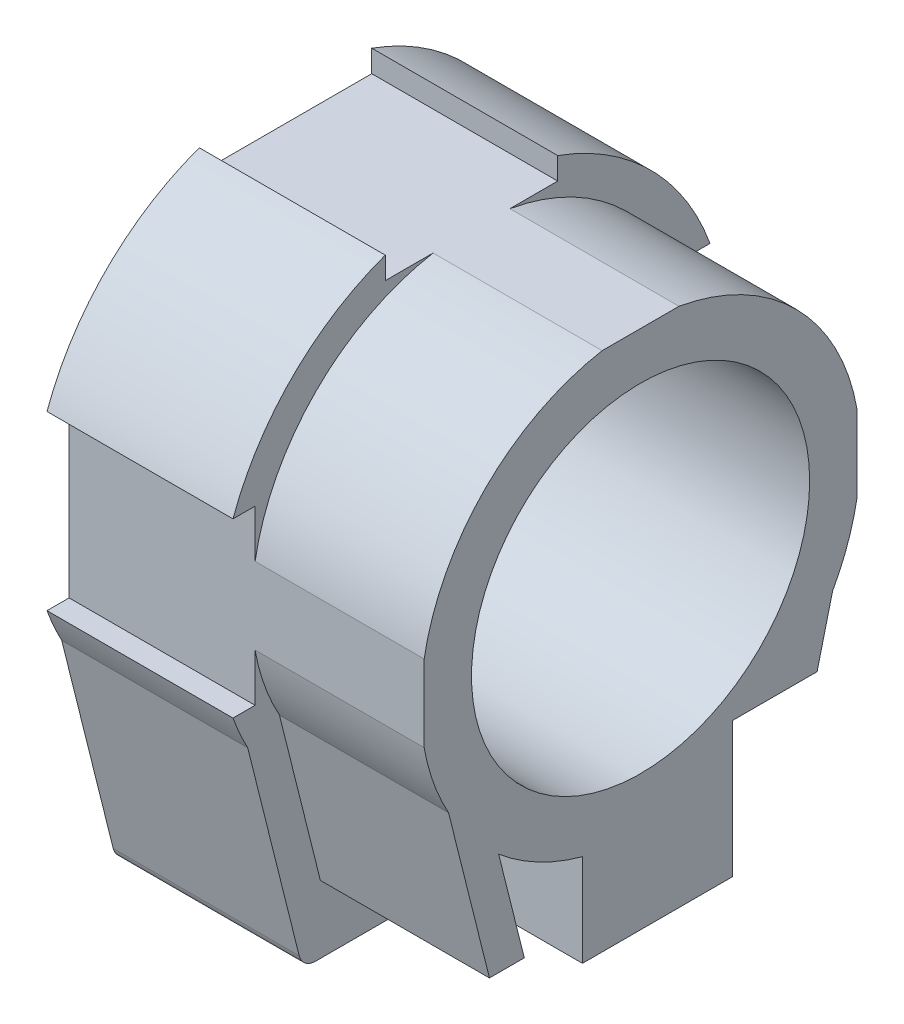
SolidWorks part; units mm, degrees
ref_plane "Alzado" through (0, 0, 0) normal (0, 0, 1) x (1, 0, 0)
ref_plane "Planta" through (0, 0, 0) normal (0, 1, 0) x (1, 0, 0)
ref_plane "Vista lateral" through (0, 0, 0) normal (1, 0, 0) x (0, 0, -1)
sketch "Croquis1" plane through (0, 0, 0) normal (1, 0, 0) x (0, 0, -1)
  line L0 (-15, 35) -> (-15, 30) construction
  line L1 (-5.7808, 0) -> (-24.2192, 0)
  line L5 (-15, 30) -> (-15, 10) construction
  line L6 (-25, 20) -> (-25, 0) construction
  line L7 (-5, 20) -> (-5, 0) construction
  line L8 (-28.2353, 12.9412) -> (-25.1894, 0.7575)
  line L9 (-1.7647, 12.9412) -> (-4.8106, 0.7575)
  circle A0 centre (-15, 20) radius 10
  arc A1 (-1.7647, 12.9412) -> (-28.2353, 12.9412) centre (-15, 20) ccw
  arc A2 (-24.2192, 0) -> (-25.1894, 0.7575) centre (-24.2192, 1) cw
  arc A3 (-5.7808, 0) -> (-4.8106, 0.7575) centre (-5.7808, 1) ccw
  dimension "D1" = 1
  dimension "D2" = 35
  dimension "D3" = 20
  dimension "D4" = 5
extrude "Saliente-Extruir1" add sketch "Croquis1" along normal blind 11
sketch "Croquis2" plane through (11, 0, 0) normal (1, 0, 0) x (0, 0, -1)
  line L9 (-23.4384, 2) -> (-6.5616, 2)
  line L10 (-6.5616, 2) -> (-3.6431, 13.6738)
  line L11 (-26.3569, 13.6738) -> (-23.4384, 2)
  line L12 (-23.4384, 2) -> (-6.5616, 2)
  line L13 (-6.5616, 2) -> (-3.6431, 13.6738)
  line L14 (-26.3569, 13.6738) -> (-23.4384, 2)
  circle A6 centre (-15, 20) radius 10 construction
  circle A7 centre (-15, 20) radius 10
  arc A9 (-3.6431, 13.6738) -> (-26.3569, 13.6738) centre (-15, 20) ccw
  arc A10 (-3.6431, 13.6738) -> (-26.3569, 13.6738) centre (-15, 20) ccw
  dimension "D1" = 2
extrude "Saliente-Extruir2" add sketch "Croquis2" along normal blind 10
sketch "Croquis3" plane through (21, 0, 0) normal (1, 0, 0) x (0, 0, -1)
  line L0 (-9.5616, 2) -> (-9.5616, 10)
  line L1 (-23.4384, 2) -> (-6.5616, 2) construction
  line L2 (-9.5616, 10) -> (-4.5616, 10)
  line L3 (-6.5616, 2) -> (-3.6431, 13.6738) construction
  line L4 (-9.5616, 2) -> (-6.5616, 2)
  line L5 (-6.5616, 2) -> (-4.5616, 10)
  line L6 (-21.7673, 2) -> (-21.7673, 4) construction
  line L7 (-23.4384, 2) -> (-18.4384, 2)
  line L8 (-23.4384, 2) -> (-23.9384, 4)
  line L9 (-21.7673, 4) -> (-21.8769, 4) construction
  line L10 (-24.4166, 14.1589) -> (-21.4982, 2.4851)
  line L11 (-23.1946, 9.2708) -> (-21.8769, 4)
  line L12 (-21.8769, 4) -> (-23.9384, 4)
  line L13 (-26.3569, 13.6738) -> (-23.4384, 2) construction
  line L14 (-18.4384, 2) -> (-18.4384, 6.9452)
  line L15 (-23.1946, 9.2708) -> (-23.3955, 10.0745)
  line L16 (-18.4384, 6.9452) -> (-18.4384, 7.463)
  circle A6 centre (-15, 20) radius 13
  arc A7 (-23.3955, 10.0745) -> (-18.4384, 7.463) centre (-15, 20) ccw
  dimension "D2" = 8
  dimension "D3" = 5
  dimension "D4" = 2
  dimension "D6" = 5
  dimension "D5" = 2
  dimension "D7" = 3
extrude "Cortar-Extruir3" cut sketch "Croquis3" against normal blind 10
sketch "Croquis8" plane through (0, 2, 0) normal (0, -1, 0) x (1, 0, 0)
  line L1 (11, 14) -> (13.2177, 14) construction
  line L2 (11, 18.4384) -> (11, 9.5616) construction
  line L4 (14.45, 14) -> (16, 14) construction
  line L5 (16, 14) -> (17.55, 14) construction
  line L7 (17.55, 14) -> (21, 14) construction
  line L8 (21, 18.4384) -> (21, 9.5616) construction
  circle A0 centre (16, 14) radius 1.55
  dimension "D2" = 3.1
extrude "Cortar-Extruir4" cut sketch "Croquis8" against normal blind 5
sketch "Croquis9" plane through (0, 0, 0) normal (-1, 0, 0) x (0, 0, 1)
  line L0 (30, 20) -> (27.8, 20) construction
  line L4 (0, 20) -> (2.2, 20) construction
  line L5 (2.2, 20) -> (2.2, 25.1)
  line L6 (2.2, 20) -> (2.2, 14.9)
  line L7 (2.2, 25.1) -> (0.8936, 25.1)
  line L8 (2.2, 14.9) -> (0.8936, 14.9)
  line L9 (15, 35) -> (15, 38.7077) construction
  line L11 (15, 35) -> (15, 32.8) construction
  line L12 (15, 32.8) -> (20.1, 32.8)
  line L13 (27.8, 14.9) -> (29.1064, 14.9)
  line L14 (27.8, 25.1) -> (29.1064, 25.1)
  line L15 (15, 32.8) -> (9.9, 32.8)
  line L16 (27.8, 20) -> (27.8, 14.9)
  line L17 (27.8, 20) -> (27.8, 25.1)
  line L18 (9.9, 32.8) -> (9.9, 34.1064)
  line L19 (20.1, 32.8) -> (20.1, 34.1064)
  arc A0 (28.2353, 12.9412) -> (1.7647, 12.9412) centre (15, 20) ccw construction
  arc A3 (29.1064, 14.9) -> (29.1064, 25.1) centre (15, 20) ccw
  arc A4 (0.8936, 25.1) -> (0.8936, 14.9) centre (15, 20) ccw
  arc A5 (20.1, 34.1064) -> (9.9, 34.1064) centre (15, 20) ccw
  dimension "D1" = 2.2
  dimension "D2" = 5.1
  dimension "D3" = 5.1
  dimension "D4" = 2.2
  dimension "D5" = 5.1
  dimension "D6" = 5.1
extrude "Cortar-Extruir5" cut sketch "Croquis9" against normal up to next
